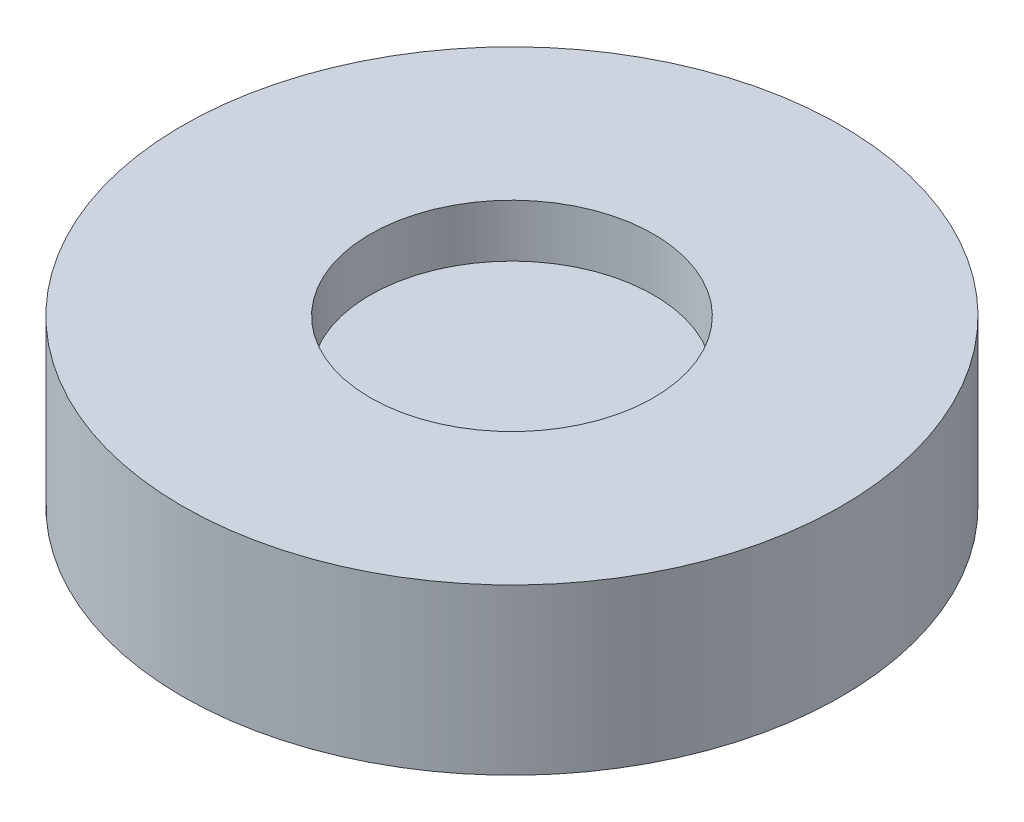
SolidWorks part; units mm, degrees
ref_plane "Front Plane" through (0, 0, 0) normal (0, 0, 1) x (1, 0, 0)
ref_plane "Top Plane" through (0, 0, 0) normal (0, 1, 0) x (1, 0, 0)
ref_plane "Right Plane" through (0, 0, 0) normal (1, 0, 0) x (0, 0, -1)
sketch "Sketch1" plane through (0, 0, 0) normal (0, 1, 0) x (1, 0, 0)
  circle A0 centre (0, 0) radius 20
  dimension "D1" = 40
extrude "Boss-Extrude1" add sketch "Sketch1" along normal blind 10
sketch "Sketch2" plane through (0, 10, 0) normal (0, 1, 0) x (1, 0, 0)
  circle A0 centre (0, 0) radius 8.6
  dimension "D1" = 17.2
extrude "Cut-Extrude2" cut sketch "Sketch2" against normal blind 3.2
sketch "Sketch3" plane through (0, 0, 0) normal (0, -1, 0) x (1, 0, 0)
  circle A0 centre (0, 0) radius 8.25
  dimension "D1" = 16.5
extrude "Cut-Extrude3" cut sketch "Sketch3" against normal blind 1.8
